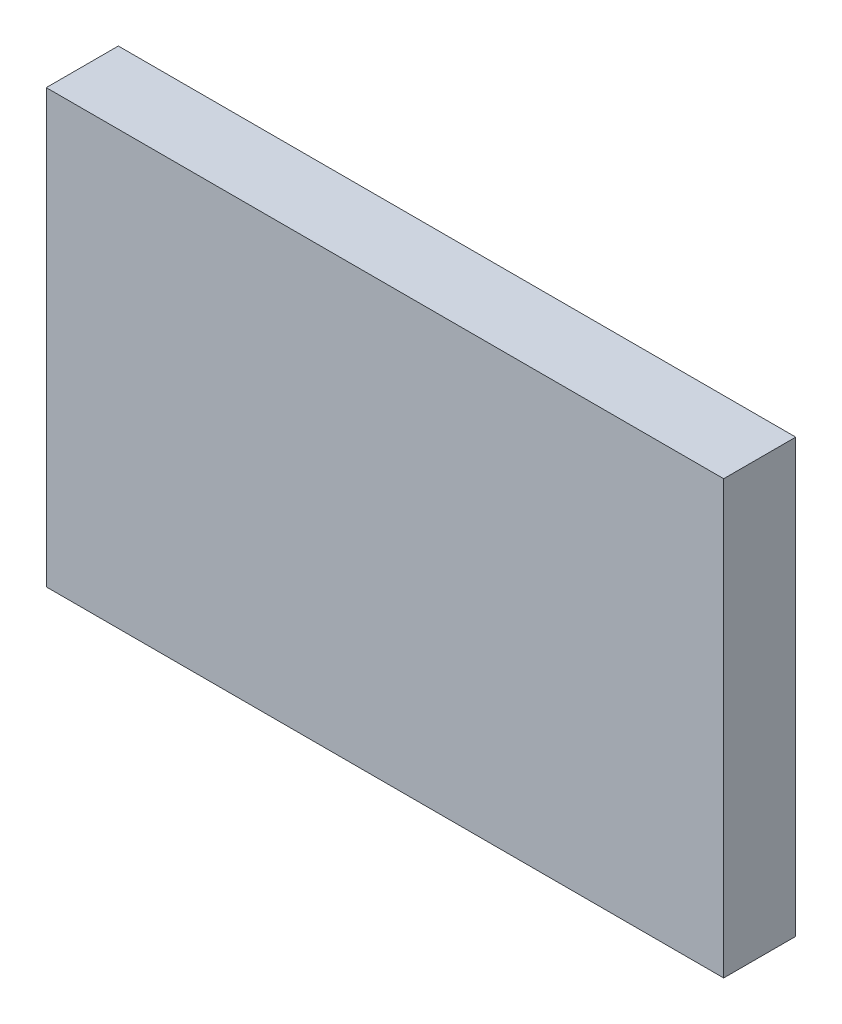
SolidWorks part; units mm, degrees
material "Q235A"
ref_plane "前视" through (0, 0, 0) normal (0, 0, 1) x (1, 0, 0)
ref_plane "上视" through (0, 0, 0) normal (0, 1, 0) x (1, 0, 0)
ref_plane "右视" through (0, 0, 0) normal (1, 0, 0) x (0, 0, -1)
sketch "草图1" plane through (0, 0, 0) normal (0, 0, 1) x (1, 0, 0)
  line L1 (47, -30) -> (-47, -30)
  line L2 (47, -30) -> (47, 30)
  line L3 (47, 30) -> (-47, 30)
  line L4 (-47, -30) -> (-47, 30)
  line L5 (47, -30) -> (-47, 30) construction
  line L6 (47, 30) -> (-47, -30) construction
  point P0 (0, 0)
  dimension "D1" = 60
  dimension "D2" = 94
extrude "凸台-拉伸1" add sketch "草图1" along normal blind 10
